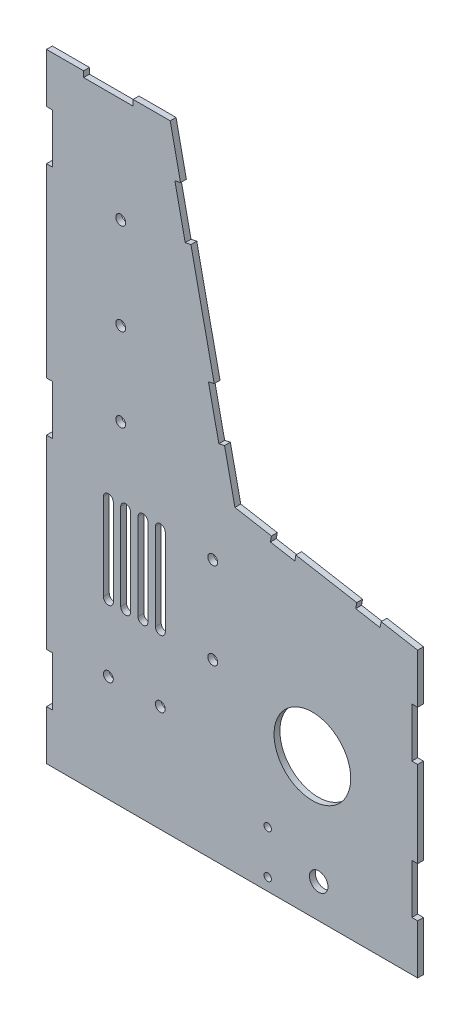
SolidWorks part; units mm, degrees
ref_plane "Front Plane" through (0, 0, 0) normal (0, 0, 1) x (1, 0, 0)
ref_plane "Top Plane" through (0, 0, 0) normal (0, 1, 0) x (1, 0, 0)
ref_plane "Right Plane" through (0, 0, 0) normal (1, 0, 0) x (0, 0, -1)
sketch "Sketch1" plane through (0, 0, 0) normal (0, 0, 1) x (1, 0, 0)
  line L6 (0, 0) -> (150, 0)
  line L27 (0, 0) -> (0, 20)
  line L28 (0, 20) -> (2.3622, 20)
  line L29 (2.3622, 20) -> (2.3622, 40)
  line L30 (2.3622, 40) -> (0, 40)
  line L31 (0, 40) -> (0, 115)
  line L32 (0, 115) -> (2.3622, 115)
  line L33 (2.3622, 115) -> (2.3622, 135)
  line L34 (2.3622, 135) -> (0, 135)
  line L35 (0, 135) -> (0, 210)
  line L36 (0, 210) -> (2.3622, 210)
  line L37 (2.3622, 210) -> (2.3622, 230)
  line L38 (2.3622, 230) -> (0, 230)
  line L39 (0, 230) -> (0, 250)
  line L40 (0, 250) -> (15, 250)
  line L41 (15, 250) -> (15, 247.6378)
  line L42 (15, 247.6378) -> (35, 247.6378)
  line L43 (35, 247.6378) -> (35, 250)
  line L44 (35, 250) -> (50, 250)
  line L46 (50, 250) -> (54.1823, 230.4422)
  line L47 (54.1823, 230.4422) -> (51.8723, 229.9482)
  line L48 (51.8723, 229.9482) -> (56.0546, 210.3904)
  line L49 (56.0546, 210.3904) -> (58.3646, 210.8844)
  line L50 (58.3646, 210.8844) -> (67.7748, 166.8793)
  line L51 (67.7748, 166.8793) -> (65.4648, 166.3853)
  line L52 (65.4648, 166.3853) -> (69.6471, 146.8275)
  line L53 (69.6471, 146.8275) -> (71.9571, 147.3214)
  line L54 (71.9571, 147.3214) -> (76.1394, 127.7636)
  line L55 (76.1394, 127.7636) -> (90.9115, 125.1589)
  line L56 (90.9115, 125.1589) -> (90.5013, 122.8326)
  line L57 (90.5013, 122.8326) -> (100.3494, 121.0961)
  line L58 (100.3494, 121.0961) -> (100.7596, 123.4224)
  line L59 (100.7596, 123.4224) -> (125.3798, 119.0812)
  line L60 (125.3798, 119.0812) -> (124.9696, 116.7549)
  line L61 (124.9696, 116.7549) -> (134.8177, 115.0184)
  line L62 (134.8177, 115.0184) -> (135.2279, 117.3447)
  line L63 (135.2279, 117.3447) -> (150, 114.74)
  line L64 (150, 114.74) -> (150, 94.74)
  line L65 (150, 94.74) -> (147.6378, 94.74)
  line L66 (147.6378, 94.74) -> (147.6378, 74.74)
  line L67 (147.6378, 74.74) -> (150, 74.74)
  line L68 (150, 74.74) -> (150, 40)
  line L69 (150, 40) -> (147.6378, 40)
  line L70 (147.6378, 40) -> (147.6378, 20)
  line L71 (147.6378, 20) -> (150, 20)
  line L72 (150, 20) -> (150, 0)
  point P20 (1.1811, 135)
  dimension "D1" = 125
  dimension "D2" = 250
  dimension "D3" = 2.3622
  dimension "D4" = 75
  dimension "D5" = 114.74
  dimension "D6" = 2.3622
  dimension "D7" = 2.3622
  dimension "D8" = 20
  dimension "D9" = 20
  dimension "D10" = 20
  dimension "D11" = 20
  dimension "D12" = 20
  dimension "D13" = 75
  dimension "D14" = 0
  dimension "D15" = 15
  dimension "D16" = 20
  dimension "D17" = 2.3622
  dimension "D18" = 127.7636
  dimension "D19" = 76.1394
  dimension "D20" = 20
  dimension "D21" = 20
  dimension "D22" = 20
  dimension "D23" = 20
  dimension "D24" = 2.3622
  dimension "D25" = 2.3622
  dimension "D26" = 15
  dimension "D27" = 2.3622
  dimension "D28" = 2.3622
  dimension "D29" = 10
  dimension "D30" = 10
  dimension "D31" = 15
  dimension "D32" = 15
  dimension "D33" = 2.3622
  dimension "D34" = 2.3622
  dimension "D35" = 2.3622
  dimension "D36" = 2.3622
  dimension "D37" = 20
  dimension "D38" = 20
  dimension "D39" = 20
  dimension "D40" = 20
  dimension "D41" = 2.3622
  dimension "D42" = 2.3622
  dimension "D43" = 2.3622
  dimension "D44" = 2.3622
extrude "Boss-Extrude1" add sketch "Sketch1" along normal blind 2.3622
sketch "Sketch2" plane through (0, 0, 2.3622) normal (0, 0, 1) x (1, 0, 0)
  line L0 (39, 105) -> (39, 70) construction
  line L1 (41, 105) -> (41, 70)
  line L2 (37, 105) -> (37, 70)
  line L3 (46, 105) -> (46, 70) construction
  line L4 (48, 105) -> (48, 70)
  line L5 (44, 105) -> (44, 70)
  line L6 (32, 105) -> (32, 70) construction
  line L7 (34, 105) -> (34, 70)
  line L8 (30, 105) -> (30, 70)
  line L9 (25, 105) -> (25, 70) construction
  line L10 (27, 105) -> (27, 70)
  line L11 (23, 105) -> (23, 70)
  line L12 (0, 0) -> (150, 0) construction
  line L13 (0, 20) -> (0, 0) construction
  line L14 (150, 0) -> (150, 20) construction
  circle A0 centre (30, 168.3018) radius 2
  arc A1 (41, 105) -> (37, 105) centre (39, 105) ccw
  arc A2 (37, 70) -> (41, 70) centre (39, 70) ccw
  arc A3 (48, 105) -> (44, 105) centre (46, 105) ccw
  arc A4 (44, 70) -> (48, 70) centre (46, 70) ccw
  arc A5 (34, 105) -> (30, 105) centre (32, 105) ccw
  arc A6 (30, 70) -> (34, 70) centre (32, 70) ccw
  arc A7 (27, 105) -> (23, 105) centre (25, 105) ccw
  arc A8 (23, 70) -> (27, 70) centre (25, 70) ccw
  circle A9 centre (67.1805, 70) radius 2
  circle A10 centre (46, 43.0147) radius 2
  circle A11 centre (67.1805, 105) radius 2
  circle A12 centre (25, 43.0147) radius 2
  circle A13 centre (30, 205.3197) radius 2
  circle A14 centre (30, 134.6424) radius 2
  circle A15 centre (110, 13.75) radius 3.75
  circle A16 centre (89.4, 22.5) radius 1.5
  circle A17 centre (89.4, 5) radius 1.5
  circle A18 centre (107.4575, 56.3172) radius 15.5
  point P4 (39, 87.5)
  point P11 (46, 87.5)
  point P18 (32, 87.5)
  point P23 (25, 87.5)
  point P52 (118.1734, 57.4257)
  point P53 (107.4575, 56.3172)
  dimension "D1" = 4
  dimension "D2" = 2
  dimension "D3" = 2
  dimension "D6" = 2
  dimension "D7" = 2
  dimension "D15" = 3
  dimension "D16" = 3
  dimension "D17" = 7.5
  dimension "D24" = 31
  dimension "D4" = 35
  dimension "D5" = 35
  dimension "D8" = 35
  dimension "D9" = 35
  dimension "D10" = 7
  dimension "D11" = 7
  dimension "D12" = 7
  dimension "D13" = 70
  dimension "D14" = 25
  dimension "D18" = 20.6
  dimension "D19" = 20.6
  dimension "D20" = 17.5
  dimension "D21" = 8.75
  dimension "D22" = 5
  dimension "D23" = 40
extrude "Cut-Extrude1" cut sketch "Sketch2" against normal through all
